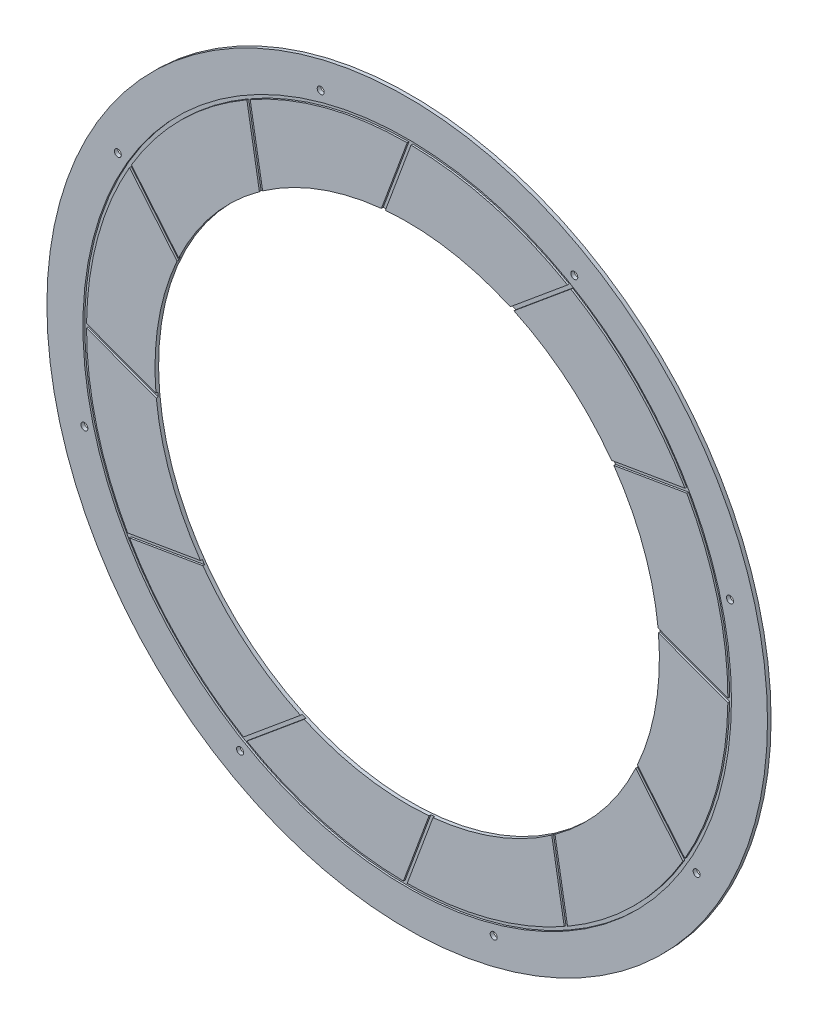
SolidWorks part; units mm, degrees
ref_plane "Front Plane" through (0, 0, 0) normal (0, 0, 1) x (1, 0, 0)
ref_plane "Top Plane" through (0, 0, 0) normal (0, 1, 0) x (1, 0, 0)
ref_plane "Right Plane" through (0, 0, 0) normal (1, 0, 0) x (0, 0, -1)
sketch "Sketch1" plane through (0, 0, 0) normal (0, 0, 1) x (1, 0, 0)
  circle A0 centre (0, 0) radius 254
  circle A2 centre (0, 0) radius 177.8
  dimension "D1" = 508
  dimension "D3" = 355.6
extrude "Boss-Extrude1" add sketch "Sketch1" along normal blind 2.54
sketch "Sketch2" plane through (0, 0, 2.54) normal (0, 0, 1) x (1, 0, 0)
  circle A0 centre (0, 0) radius 228.6
  circle A1 centre (0, 0) radius 226.06
  dimension "D1" = 457.2
  dimension "D2" = 452.12
extrude "Cut-Extrude1" cut sketch "Sketch2" against normal blind 1.27
sketch "Sketch4" plane through (0, 0, 2.54) normal (0, 0, 1) x (1, 0, 0)
  line L0 (0, 0) -> (-286.1423, 0) construction
  line L1 (-226.06, 0) -> (-176.1254, -18.4798)
  line L2 (-176.1254, -18.4798) -> (-175.2438, -16.0976)
  line L3 (-175.2438, -16.0976) -> (-226.0438, 2.7024)
  line L4 (-195.7737, 113.03) -> (-161.769, 72.0588)
  line L5 (-161.769, 72.0588) -> (-159.8144, 73.681)
  line L6 (-159.8144, 73.681) -> (-194.4085, 115.3623)
  line L7 (-113.03, 195.7737) -> (-104.0666, 143.2892)
  line L8 (-104.0666, 143.2892) -> (-101.5629, 143.7168)
  line L9 (-101.5629, 143.7168) -> (-110.6816, 197.1109)
  line L10 (0, 226.06) -> (-18.4798, 176.1254)
  line L11 (-18.4798, 176.1254) -> (-16.0976, 175.2438)
  line L12 (-16.0976, 175.2438) -> (2.7024, 226.0438)
  line L13 (113.03, 195.7737) -> (72.0588, 161.769)
  line L14 (72.0588, 161.769) -> (73.681, 159.8144)
  line L15 (73.681, 159.8144) -> (115.3623, 194.4085)
  line L16 (195.7737, 113.03) -> (143.2892, 104.0666)
  line L17 (143.2892, 104.0666) -> (143.7168, 101.5629)
  line L18 (143.7168, 101.5629) -> (197.1109, 110.6816)
  line L19 (226.06, 0) -> (176.1254, 18.4798)
  line L20 (176.1254, 18.4798) -> (175.2438, 16.0976)
  line L21 (175.2438, 16.0976) -> (226.0438, -2.7024)
  line L22 (195.7737, -113.03) -> (161.769, -72.0588)
  line L23 (161.769, -72.0588) -> (159.8144, -73.681)
  line L24 (159.8144, -73.681) -> (194.4085, -115.3623)
  line L25 (113.03, -195.7737) -> (104.0666, -143.2892)
  line L26 (104.0666, -143.2892) -> (101.5629, -143.7168)
  line L27 (101.5629, -143.7168) -> (110.6816, -197.1109)
  line L28 (0, -226.06) -> (18.4798, -176.1254)
  line L29 (18.4798, -176.1254) -> (16.0976, -175.2438)
  line L30 (16.0976, -175.2438) -> (-2.7024, -226.0438)
  line L31 (-113.03, -195.7737) -> (-72.0588, -161.769)
  line L32 (-72.0588, -161.769) -> (-73.681, -159.8144)
  line L33 (-73.681, -159.8144) -> (-115.3623, -194.4085)
  line L34 (-195.7737, -113.03) -> (-143.2892, -104.0666)
  line L35 (-143.2892, -104.0666) -> (-143.7168, -101.5629)
  line L36 (-143.7168, -101.5629) -> (-197.1109, -110.6816)
  circle A0 centre (0, 0) radius 226.06 construction
  arc A1 (-226.0438, 2.7024) -> (-226.06, 0) centre (0, 0) ccw
  arc A2 (-194.4085, 115.3623) -> (-195.7737, 113.03) centre (0, 0) ccw
  arc A3 (-110.6816, 197.1109) -> (-113.03, 195.7737) centre (0, 0) ccw
  arc A4 (2.7024, 226.0438) -> (0, 226.06) centre (0, 0) ccw
  arc A5 (115.3623, 194.4085) -> (113.03, 195.7737) centre (0, 0) ccw
  arc A6 (197.1109, 110.6816) -> (195.7737, 113.03) centre (0, 0) ccw
  arc A7 (226.0438, -2.7024) -> (226.06, 0) centre (0, 0) ccw
  arc A8 (194.4085, -115.3623) -> (195.7737, -113.03) centre (0, 0) ccw
  arc A9 (110.6816, -197.1109) -> (113.03, -195.7737) centre (0, 0) ccw
  arc A10 (-2.7024, -226.0438) -> (0, -226.06) centre (0, 0) ccw
  arc A11 (-115.3623, -194.4085) -> (-113.03, -195.7737) centre (0, 0) ccw
  arc A12 (-197.1109, -110.6816) -> (-195.7737, -113.03) centre (0, 0) ccw
  dimension "D1" = 2.54
  dimension "D3" = 50.8
  dimension "D2" = 12
extrude "Cut-Extrude2" cut sketch "Sketch4" against normal blind 1.27
hole_wizard "#10 (0.1935) Diameter Hole2" positions "Sketch9" profile "Sketch10" hole size "#10" standard "ANSI Inch" end condition through all
sketch "Sketch9" plane through (0, 0, 2.54) normal (0, 0, 1) x (1, 0, 0)
  line L1 (0, 0) -> (-342.3182, 0) construction
  line L3 (-204.0226, 117.7925) -> (0, 0) construction
  point P0 (-204.0226, 117.7925)
  point P19 (-60.9739, 227.5576)
  point P20 (117.7925, 204.0226)
  point P21 (227.5576, 60.9739)
  point P22 (204.0226, -117.7925)
  point P23 (60.9739, -227.5576)
  point P24 (-117.7925, -204.0226)
  point P25 (-227.5576, -60.9739)
  dimension "D1" = 235.585
  dimension "D2" = 30
  dimension "D3" = 8
sketch "Sketch10" plane through (-204.0226, 117.7925, 2.54) normal (1, 0, 0) x (0, -1, 0)
  line L0 (0, 0) -> (0, 2.54)
  line L1 (0, 2.54) -> (2.4574, 2.54)
  line L2 (2.4574, 2.54) -> (2.4574, 0)
  line L5 (2.4574, 0) -> (0, 0)
  line L11 (0, -6.35) -> (0, 107.95) construction
  dimension "Thru Hole Dia." = 4.9149
  dimension "Thru Hole Depth" = 2.54
hole_wizard "#10 (0.1935) Diameter Hole1" positions "Sketch7" profile "Sketch8" hole size "#10" standard "ANSI Inch"
sketch "Sketch7" plane through (0, 0, 2.54) normal (0, 0, 1) x (1, 0, 0)
  point P0 (-241.3, 0)
  point P8 (-170.6249, 170.6249)
  point P9 (0, 241.3)
  point P10 (170.6249, 170.6249)
  point P11 (241.3, 0)
  point P12 (170.6249, -170.6249)
  point P13 (0, -241.3)
  point P14 (-170.6249, -170.6249)
  dimension "D1" = 241.3
  dimension "D2" = 8
sketch "Sketch8" plane through (-241.3, 0, 2.54) normal (1, 0, 0) x (0, -1, 0)
  line L0 (0, 0) -> (0, 2.54)
  line L1 (0, 2.54) -> (2.4574, 2.54)
  line L2 (2.4574, 2.54) -> (2.4574, 0)
  line L5 (2.4574, 0) -> (0, 0)
  line L11 (0, -6.35) -> (0, 107.95) construction
  dimension "Thru Hole Dia." = 4.9149
  dimension "Thru Hole Depth" = 2.54
